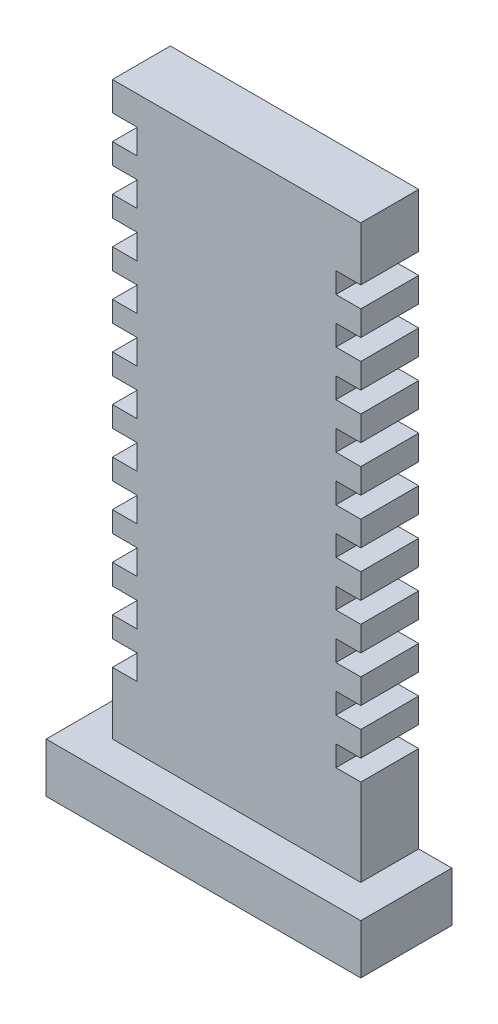
SolidWorks part; units mm, degrees
ref_plane "Front Plane" through (0, 0, 0) normal (0, 0, 1) x (1, 0, 0)
ref_plane "Top Plane" through (0, 0, 0) normal (0, 1, 0) x (1, 0, 0)
ref_plane "Right Plane" through (0, 0, 0) normal (1, 0, 0) x (0, 0, -1)
sketch "Sketch1" plane through (0, 0, 0) normal (0, 0, 1) x (1, 0, 0)
  line L1 (-30, 0) -> (30, 0)
  line L2 (-30, 0) -> (-30, 150)
  line L3 (-30, 150) -> (30, 150)
  line L4 (30, 0) -> (30, 150)
  line L5 (-30, 0) -> (30, 150) construction
  line L6 (-30, 150) -> (30, 0) construction
  point P4 (0, 75)
extrude "BridgePlate" add sketch "Sketch1" along normal blind 14
sketch "Sketch9" plane through (0, 0, 14) normal (0, 0, 1) x (1, 0, 0)
  line L1 (-33, 27) -> (-24, 27)
  line L2 (-33, 27) -> (-33, 33)
  line L3 (-33, 33) -> (-24, 33)
  line L4 (-24, 27) -> (-24, 33)
  line L5 (-33, 27) -> (-24, 33) construction
  line L6 (-33, 33) -> (-24, 27) construction
  line L7 (-33, 38) -> (-24, 38)
  line L8 (-33, 38) -> (-33, 44)
  line L9 (-33, 44) -> (-24, 44)
  line L10 (-24, 38) -> (-24, 44)
  line L11 (-33, 38) -> (-24, 44) construction
  line L12 (-33, 44) -> (-24, 38) construction
  line L13 (-33, 49) -> (-24, 49)
  line L14 (-33, 49) -> (-33, 55)
  line L15 (-33, 55) -> (-24, 55)
  line L16 (-24, 49) -> (-24, 55)
  line L17 (-33, 49) -> (-24, 55) construction
  line L18 (-33, 55) -> (-24, 49) construction
  line L19 (-33, 60) -> (-24, 60)
  line L20 (-33, 60) -> (-33, 66)
  line L21 (-33, 66) -> (-24, 66)
  line L22 (-24, 60) -> (-24, 66)
  line L23 (-33, 60) -> (-24, 66) construction
  line L24 (-33, 66) -> (-24, 60) construction
  line L25 (-33, 71) -> (-24, 71)
  line L26 (-33, 71) -> (-33, 77)
  line L27 (-33, 77) -> (-24, 77)
  line L28 (-24, 71) -> (-24, 77)
  line L29 (-33, 71) -> (-24, 77) construction
  line L30 (-33, 77) -> (-24, 71) construction
  line L31 (-33, 82) -> (-24, 82)
  line L32 (-33, 82) -> (-33, 88)
  line L33 (-33, 88) -> (-24, 88)
  line L34 (-24, 82) -> (-24, 88)
  line L35 (-33, 82) -> (-24, 88) construction
  line L36 (-33, 88) -> (-24, 82) construction
  line L37 (-33, 93) -> (-24, 93)
  line L38 (-33, 93) -> (-33, 99)
  line L39 (-33, 99) -> (-24, 99)
  line L40 (-24, 93) -> (-24, 99)
  line L41 (-33, 93) -> (-24, 99) construction
  line L42 (-33, 99) -> (-24, 93) construction
  line L43 (-33, 104) -> (-24, 104)
  line L44 (-33, 104) -> (-33, 110)
  line L45 (-33, 110) -> (-24, 110)
  line L46 (-24, 104) -> (-24, 110)
  line L47 (-33, 104) -> (-24, 110) construction
  line L48 (-33, 110) -> (-24, 104) construction
  line L49 (-33, 115) -> (-24, 115)
  line L50 (-33, 115) -> (-33, 121)
  line L51 (-33, 121) -> (-24, 121)
  line L52 (-24, 115) -> (-24, 121)
  line L53 (-33, 115) -> (-24, 121) construction
  line L54 (-33, 121) -> (-24, 115) construction
  line L55 (-33, 126) -> (-24, 126)
  line L56 (-33, 126) -> (-33, 132)
  line L57 (-33, 132) -> (-24, 132)
  line L58 (-24, 126) -> (-24, 132)
  line L59 (-33, 126) -> (-24, 132) construction
  line L60 (-33, 132) -> (-24, 126) construction
  line L61 (-33, 137) -> (-24, 137)
  line L62 (-33, 137) -> (-33, 143)
  line L63 (-33, 143) -> (-24, 143)
  line L64 (-24, 137) -> (-24, 143)
  line L65 (-33, 137) -> (-24, 143) construction
  line L66 (-33, 143) -> (-24, 137) construction
  line L67 (33, 33) -> (24, 33)
  line L68 (33, 33) -> (33, 38)
  line L69 (33, 38) -> (24, 38)
  line L70 (24, 33) -> (24, 38)
  line L71 (33, 33) -> (24, 38) construction
  line L72 (33, 38) -> (24, 33) construction
  line L73 (33, 44) -> (24, 44)
  line L74 (33, 44) -> (33, 49)
  line L75 (33, 49) -> (24, 49)
  line L76 (24, 44) -> (24, 49)
  line L77 (33, 44) -> (24, 49) construction
  line L78 (33, 49) -> (24, 44) construction
  line L79 (33, 55) -> (24, 55)
  line L80 (33, 55) -> (33, 60)
  line L81 (33, 60) -> (24, 60)
  line L82 (24, 55) -> (24, 60)
  line L83 (33, 55) -> (24, 60) construction
  line L84 (33, 60) -> (24, 55) construction
  line L85 (33, 66) -> (24, 66)
  line L86 (33, 66) -> (33, 71)
  line L87 (33, 71) -> (24, 71)
  line L88 (24, 66) -> (24, 71)
  line L89 (33, 66) -> (24, 71) construction
  line L90 (33, 71) -> (24, 66) construction
  line L91 (33, 77) -> (24, 77)
  line L92 (33, 77) -> (33, 82)
  line L93 (33, 82) -> (24, 82)
  line L94 (24, 77) -> (24, 82)
  line L95 (33, 77) -> (24, 82) construction
  line L96 (33, 82) -> (24, 77) construction
  line L97 (33, 88) -> (24, 88)
  line L98 (33, 88) -> (33, 93)
  line L99 (33, 93) -> (24, 93)
  line L100 (24, 88) -> (24, 93)
  line L101 (33, 88) -> (24, 93) construction
  line L102 (33, 93) -> (24, 88) construction
  line L103 (33, 99) -> (24, 99)
  line L104 (33, 99) -> (33, 104)
  line L105 (33, 104) -> (24, 104)
  line L106 (24, 99) -> (24, 104)
  line L107 (33, 99) -> (24, 104) construction
  line L108 (33, 104) -> (24, 99) construction
  line L109 (33, 110) -> (24, 110)
  line L110 (33, 110) -> (33, 115)
  line L111 (33, 115) -> (24, 115)
  line L112 (24, 110) -> (24, 115)
  line L113 (33, 110) -> (24, 115) construction
  line L114 (33, 115) -> (24, 110) construction
  line L115 (33, 121) -> (24, 121)
  line L116 (33, 121) -> (33, 126)
  line L117 (33, 126) -> (24, 126)
  line L118 (24, 121) -> (24, 126)
  line L119 (33, 121) -> (24, 126) construction
  line L120 (33, 126) -> (24, 121) construction
  line L121 (33, 132) -> (24, 132)
  line L122 (33, 132) -> (33, 137)
  line L123 (33, 137) -> (24, 137)
  line L124 (24, 132) -> (24, 137)
  line L125 (33, 132) -> (24, 137) construction
  line L126 (33, 137) -> (24, 132) construction
  point P4 (-28.5, 30)
  point P9 (-28.5, 41)
  point P14 (-28.5, 52)
  point P19 (-28.5, 63)
  point P24 (-28.5, 74)
  point P29 (-28.5, 85)
  point P34 (-28.5, 96)
  point P39 (-28.5, 107)
  point P44 (-28.5, 118)
  point P49 (-28.5, 129)
  point P54 (-28.5, 140)
  point P59 (28.5, 35.5)
  point P64 (28.5, 46.5)
  point P69 (28.5, 57.5)
  point P74 (28.5, 68.5)
  point P79 (28.5, 79.5)
  point P84 (28.5, 90.5)
  point P89 (28.5, 101.5)
  point P94 (28.5, 112.5)
  point P99 (28.5, 123.5)
  point P104 (28.5, 134.5)
extrude "StringNotches" cut sketch "Sketch9" against normal through all
sketch "Sketch10" plane through (0, 0, 0) normal (0, 0, 1) x (1, 0, 0)
  line L1 (-38, 0) -> (38, 0)
  line L2 (-38, 0) -> (-38, 12)
  line L3 (-38, 12) -> (38, 12)
  line L4 (38, 0) -> (38, 12)
  line L5 (-38, 0) -> (38, 12) construction
  line L6 (-38, 12) -> (38, 0) construction
  point P4 (0, 6)
extrude "BridgeFoot" add sketch "Sketch10" along normal blind 22
